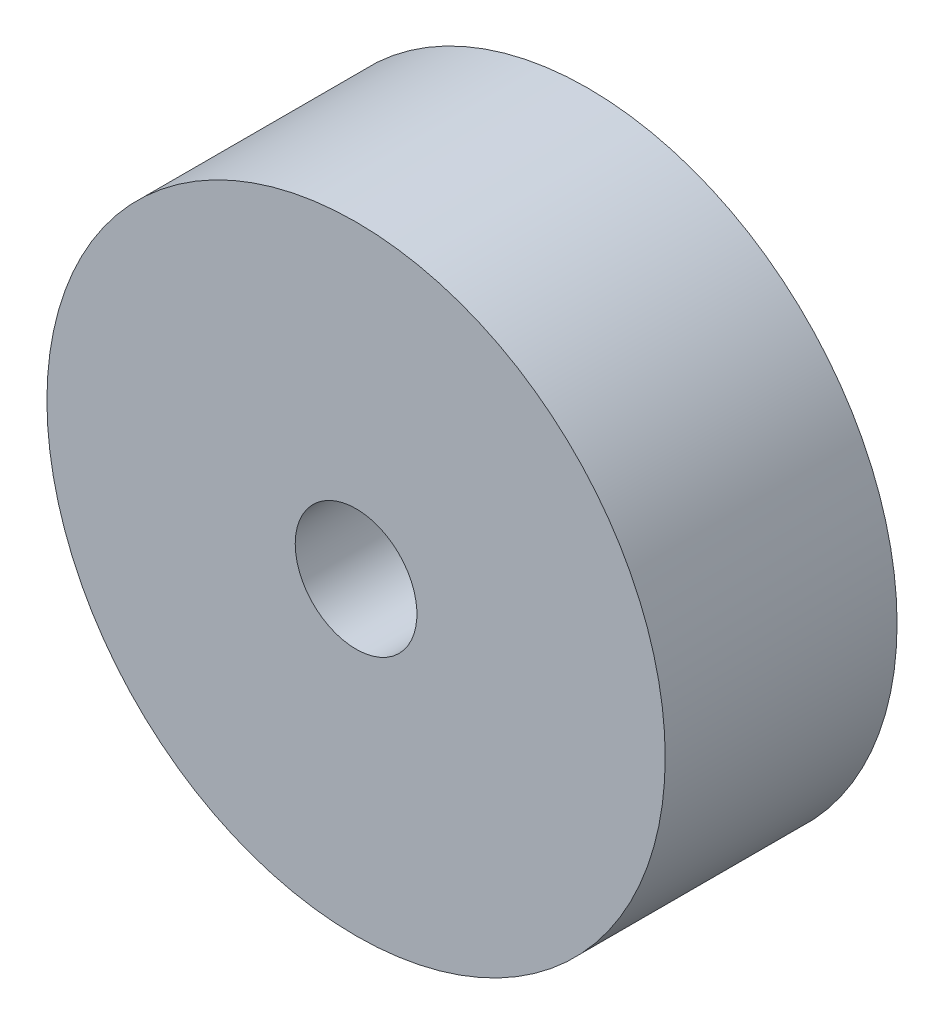
SolidWorks part; units mm, degrees
material "Polyurethane Foam Rigid"
ref_plane "Front Plane" through (0, 0, 0) normal (0, 0, 1) x (1, 0, 0)
ref_plane "Top Plane" through (0, 0, 0) normal (0, 1, 0) x (1, 0, 0)
ref_plane "Right Plane" through (0, 0, 0) normal (1, 0, 0) x (0, 0, -1)
sketch "Sketch1" plane through (0, 0, 0) normal (0, 0, 1) x (1, 0, 0)
  circle A0 centre (0, 0) radius 25.4
  circle A1 centre (0, 0) radius 5
  dimension "D1" = 10
  dimension "D2" = 50.8
extrude "Boss-Extrude1" add sketch "Sketch1" along normal mid plane 19.05
equation "\"D2@Sketch1\"=2in"
equation "\"D1@Boss-Extrude1\"=0.75in"
